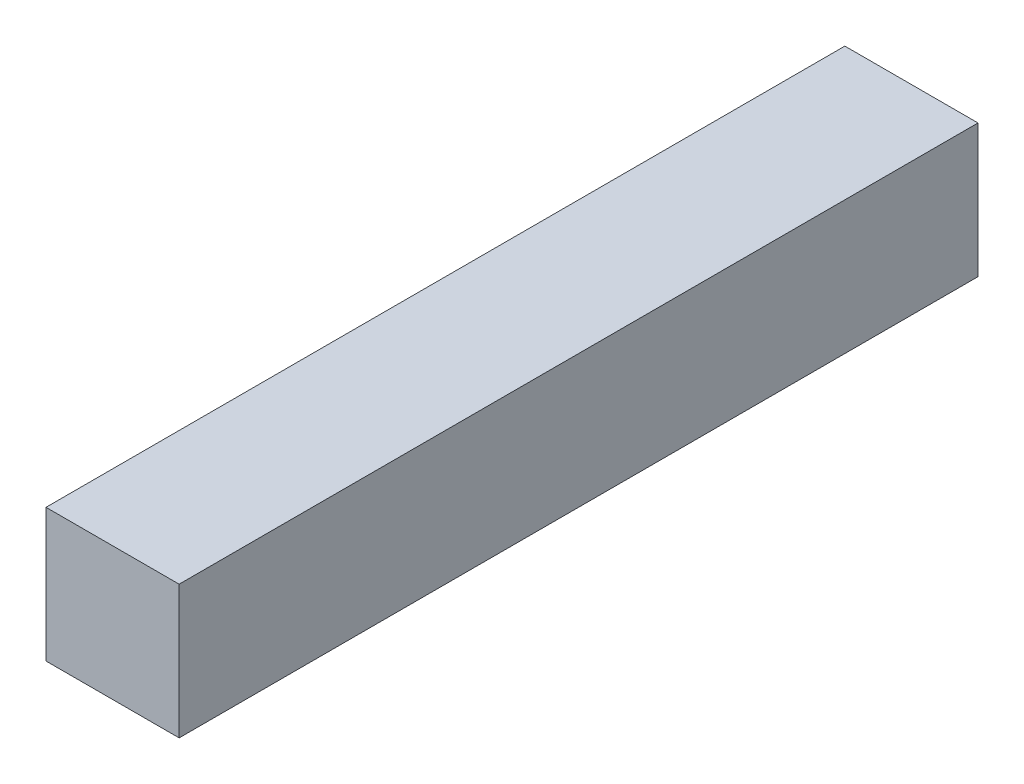
SolidWorks part; units mm, degrees
ref_plane "Front Plane" through (0, 0, 0) normal (0, 0, 1) x (1, 0, 0)
ref_plane "Top Plane" through (0, 0, 0) normal (0, 1, 0) x (1, 0, 0)
ref_plane "Right Plane" through (0, 0, 0) normal (1, 0, 0) x (0, 0, -1)
sketch "Sketch1" plane through (0, 0, 0) normal (0, 0, 1) x (1, 0, 0)
  line L0 (0, 3.175) -> (0, -3.175)
  line L1 (-3.175, 0) -> (3.175, 0) construction
  point P6 (0, 0)
  dimension "Width" = 6.35
  dimension "Thk" = 6.35
sketch "Sketch2" plane through (0, 0, 0) normal (1, 0, 0) x (0, 0, -1)
  line L0 (19.05, 0) -> (-19.05, 0)
  point P4 (0, 0)
  dimension "Length" = 38.1
sketch "Sketch3" plane through (0, 0, 0) normal (0, 0, 1) x (1, 0, 0)
  line L1 (3.175, 3.175) -> (-3.175, 3.175)
  line L2 (3.175, 3.175) -> (3.175, -3.175)
  line L3 (3.175, -3.175) -> (-3.175, -3.175)
  line L4 (-3.175, 3.175) -> (-3.175, -3.175)
  line L5 (3.175, 3.175) -> (-3.175, -3.175) construction
  line L6 (3.175, -3.175) -> (-3.175, 3.175) construction
  point P0 (0, 0)
extrude "Boss-Extrude1" add sketch "Sketch3" along normal up to vertex (19.05 mm away) and the other way up to vertex (19.05 mm away) up to point (0, 0, 19.05) other way up to point (0, 0, -19.05)
